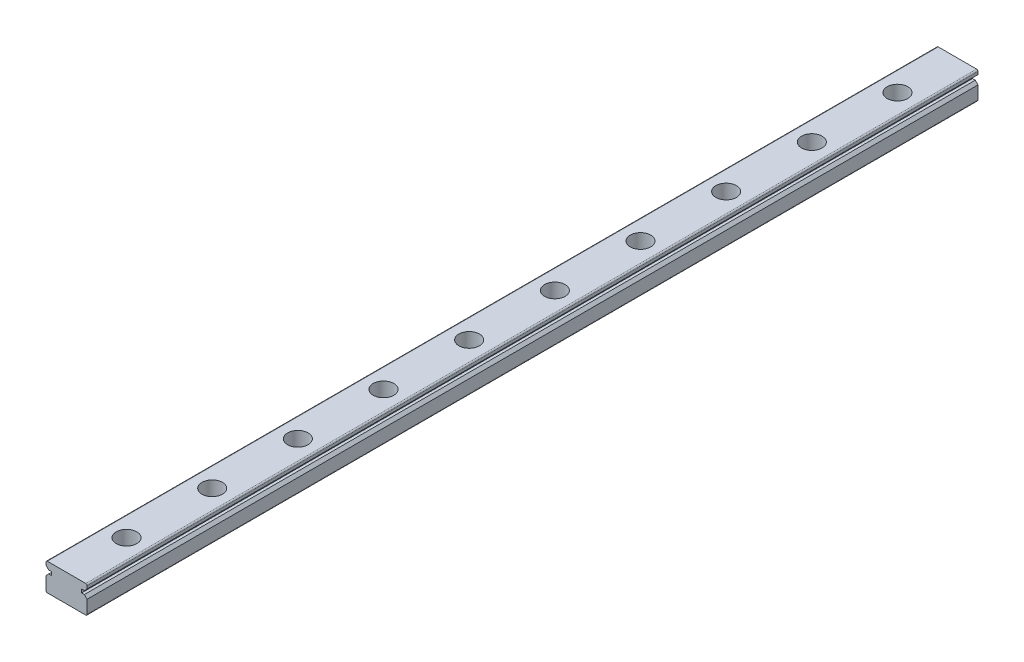
SolidWorks part; units mm, degrees
ref_plane "Front Plane" through (0, 0, 0) normal (0, 0, 1) x (1, 0, 0)
ref_plane "Top Plane" through (0, 0, 0) normal (0, 1, 0) x (1, 0, 0)
ref_plane "Right Plane" through (0, 0, 0) normal (1, 0, 0) x (0, 0, -1)
sketch "Sketch1" plane through (0, 0, 0) normal (0, 0, 1) x (1, 0, 0)
  line L0 (0, -1000) -> (0, 1.5) construction
  line L1 (-5.6, 4) -> (5.6, 4)
  line L2 (-6, 3.6) -> (-6, 2.8)
  line L3 (-5.6, -4) -> (5.6, -4)
  line L4 (6, 3.6) -> (6, 2.8)
  line L5 (-6, 4) -> (6, -4) construction
  line L6 (-6, -4) -> (6, 4) construction
  line L7 (6, 0.2) -> (6, -3.6)
  line L8 (-5.2, 2) -> (-4.4, 2)
  line L9 (-4.4, 2) -> (-4.4, 1)
  line L10 (-5.2, 1) -> (-4.4, 1)
  line L11 (4.4, 2) -> (4.4, 1)
  line L14 (-6, 0.2) -> (-6, -3.6)
  line L15 (4.4, 2) -> (5.2, 2)
  line L16 (4.4, 1) -> (5.2, 1)
  line L17 (0, 1.5) -> (0, 1001.8645) construction
  line L18 (-6, 2.8) -> (-5.2, 2)
  line L19 (-6, 0.2) -> (-5.2, 1)
  line L20 (5.2, 2) -> (6, 2.8)
  line L21 (5.2, 1) -> (6, 0.2)
  arc A0 (-6, -3.6) -> (-5.6, -4) centre (-5.6, -3.6) ccw
  arc A1 (5.6, -4) -> (6, -3.6) centre (5.6, -3.6) ccw
  arc A2 (5.6, 4) -> (6, 3.6) centre (5.6, 3.6) cw
  arc A3 (-5.6, 4) -> (-6, 3.6) centre (-5.6, 3.6) ccw
  point P0 (0, 0)
  point P13 (-6, 2)
  point P14 (6, 2)
  point P15 (6, 1)
  point P16 (-6, 1)
  dimension "D5" = 0.4
  dimension "D1" = 12
  dimension "D2" = 8
  dimension "D3" = 8.8
  dimension "D4" = 5
  dimension "D6" = 2
  dimension "D7" = 5
  dimension "D8" = 4.4
extrude "Boss-Extrude1" add sketch "Sketch1" along normal blind 260
sketch "Sketch2" plane through (0, 4, 0) normal (0, 1, 0) x (1, 0, 0)
  line L0 (5.6, -260) -> (-5.6, -260) construction
  circle A0 centre (0, -242.5) radius 3
  circle A1 centre (0, -217.5) radius 3
  circle A2 centre (0, -192.5) radius 3
  circle A3 centre (0, -167.5) radius 3
  circle A4 centre (0, -142.5) radius 3
  circle A5 centre (0, -117.5) radius 3
  circle A6 centre (0, -92.5) radius 3
  circle A7 centre (0, -67.5) radius 3
  circle A8 centre (0, -42.5) radius 3
  circle A9 centre (0, -17.5) radius 3
  circle A10 centre (0, 7.5) radius 3
  circle A11 centre (0, 32.5) radius 3
  circle A12 centre (0, 57.5) radius 3
  circle A13 centre (0, 82.5) radius 3
  circle A14 centre (0, 107.5) radius 3
  circle A15 centre (0, 132.5) radius 3
  circle A16 centre (0, 157.5) radius 3
  circle A17 centre (0, 182.5) radius 3
  point P39 (0, -260)
  dimension "D1" = 17.5
  dimension "D2" = 6
  dimension "D3" = 18
extrude "Cut-Extrude1" cut sketch "Sketch2" against normal blind 4.5
sketch "Sketch3" plane through (0, 4, 0) normal (0, 1, 0) x (1, 0, 0)
  line L0 (5.6, -260) -> (-5.6, -260) construction
  circle A2 centre (0, -242.5) radius 1.75
  circle A3 centre (0, -217.5) radius 1.75
  circle A4 centre (0, -192.5) radius 1.75
  circle A5 centre (0, -167.5) radius 1.75
  circle A6 centre (0, -142.5) radius 1.75
  circle A7 centre (0, -117.5) radius 1.75
  circle A8 centre (0, -92.5) radius 1.75
  circle A9 centre (0, -67.5) radius 1.75
  circle A10 centre (0, -42.5) radius 1.75
  circle A11 centre (0, -17.5) radius 1.75
  circle A12 centre (0, 7.5) radius 1.75
  circle A13 centre (0, 32.5) radius 1.75
  circle A14 centre (0, 57.5) radius 1.75
  circle A15 centre (0, 82.5) radius 1.75
  circle A16 centre (0, 107.5) radius 1.75
  point P6 (0, -260)
  dimension "D1" = 3.5
  dimension "D2" = 17.5
  dimension "D3" = 15
extrude "Cut-Extrude2" cut sketch "Sketch3" against normal through all
